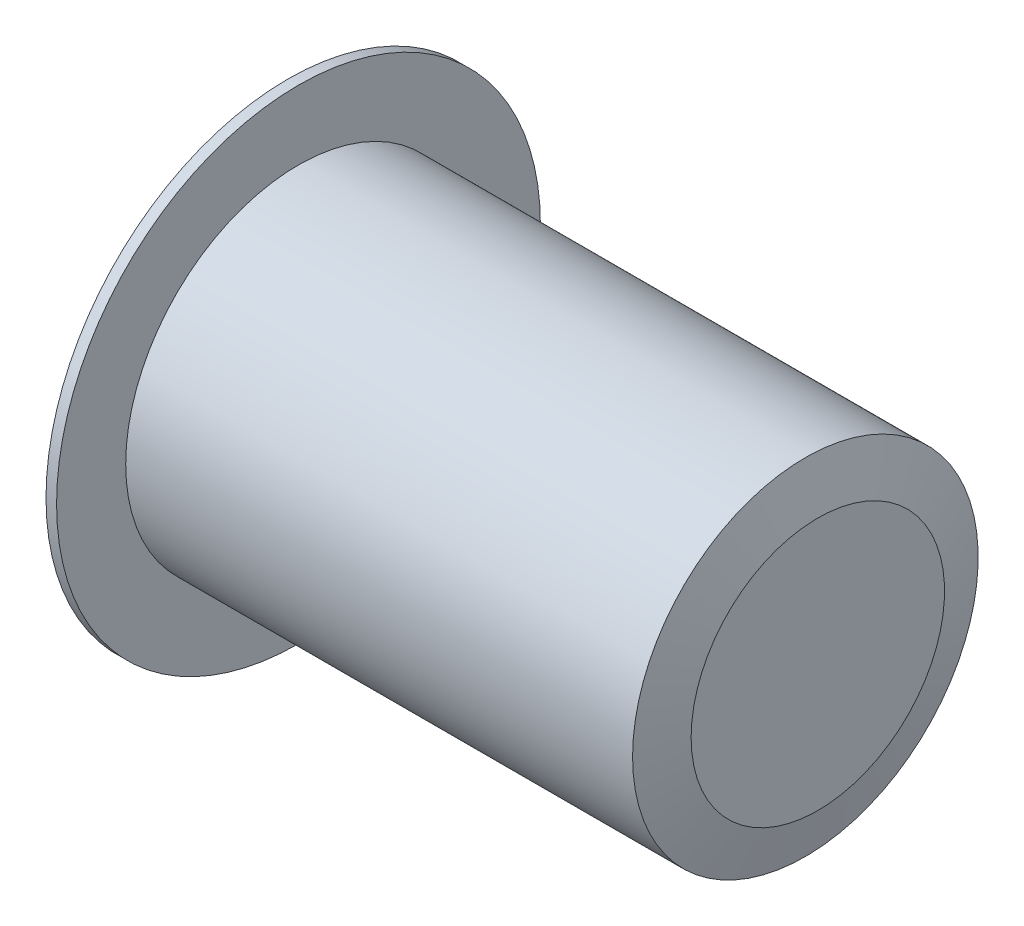
SolidWorks part; units mm, degrees
ref_plane "Plan de face" through (0, 0, 0) normal (0, 0, 1) x (1, 0, 0)
ref_plane "Plan de dessus" through (0, 0, 0) normal (0, 1, 0) x (1, 0, 0)
ref_plane "Plan de droite" through (0, 0, 0) normal (1, 0, 0) x (0, 0, -1)
sketch "Esquisse1" plane through (0, 0, 0) normal (0, 0, 1) x (1, 0, 0)
  line L0 (0, 0) -> (230, 0)
  line L1 (0, 105) -> (0, 30)
  line L2 (0, 30) -> (180, 30)
  line L3 (180, 30) -> (180, 0)
  line L6 (0, 105) -> (4.5905, 105)
  line L7 (4.5905, 105) -> (4.5905, 75)
  line L8 (4.5905, 75) -> (224.5905, 75)
  line L9 (224.5905, 75) -> (230, 55)
  line L10 (230, 55) -> (230, 0)
  line L11 (0, 0) -> (230, 0) construction
  dimension "D1" = 230
  dimension "D2" = 110
  dimension "D3" = 150
  dimension "D4" = 30
  dimension "D5" = 220
  dimension "D6" = 4.5905
  dimension "D7" = 180
  dimension "D8" = 30
revolve "Révolution1" add sketch "Esquisse1" angle 360 about L11
